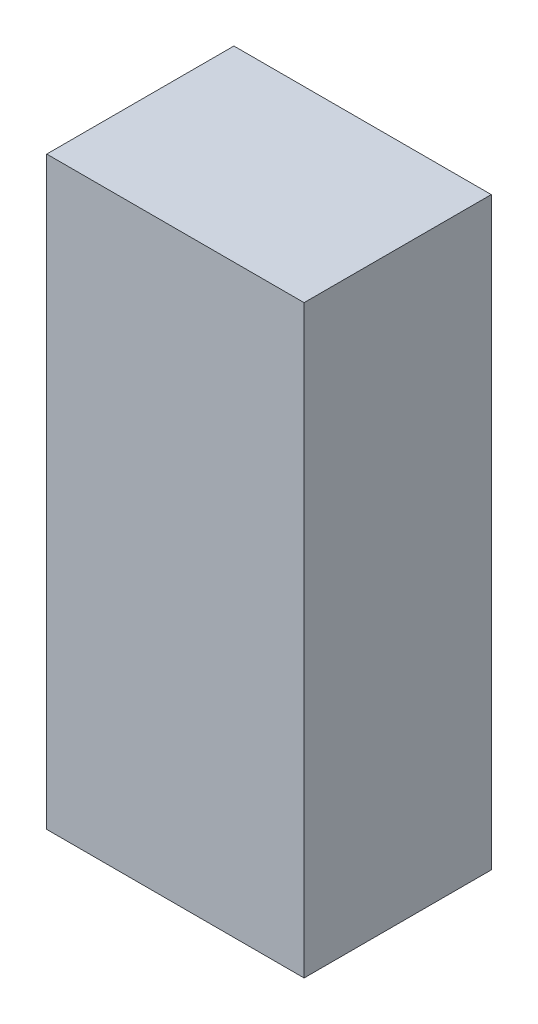
SolidWorks part; units mm, degrees
ref_plane "Front Plane" through (0, 0, 0) normal (0, 0, 1) x (1, 0, 0)
ref_plane "Top Plane" through (0, 0, 0) normal (0, 1, 0) x (1, 0, 0)
ref_plane "Right Plane" through (0, 0, 0) normal (1, 0, 0) x (0, 0, -1)
sketch "Sketch1" plane through (0, 0, 0) normal (0, 0, 1) x (1, 0, 0)
  line L1 (-33, -75) -> (33, -75)
  line L2 (-33, -75) -> (-33, 75)
  line L3 (-33, 75) -> (33, 75)
  line L4 (33, -75) -> (33, 75)
  line L5 (-33, -75) -> (33, 75) construction
  line L6 (-33, 75) -> (33, -75) construction
  point P0 (0, 0)
  dimension "D1" = 150
  dimension "D2" = 66
extrude "Boss-Extrude1" add sketch "Sketch1" along normal mid plane 48
